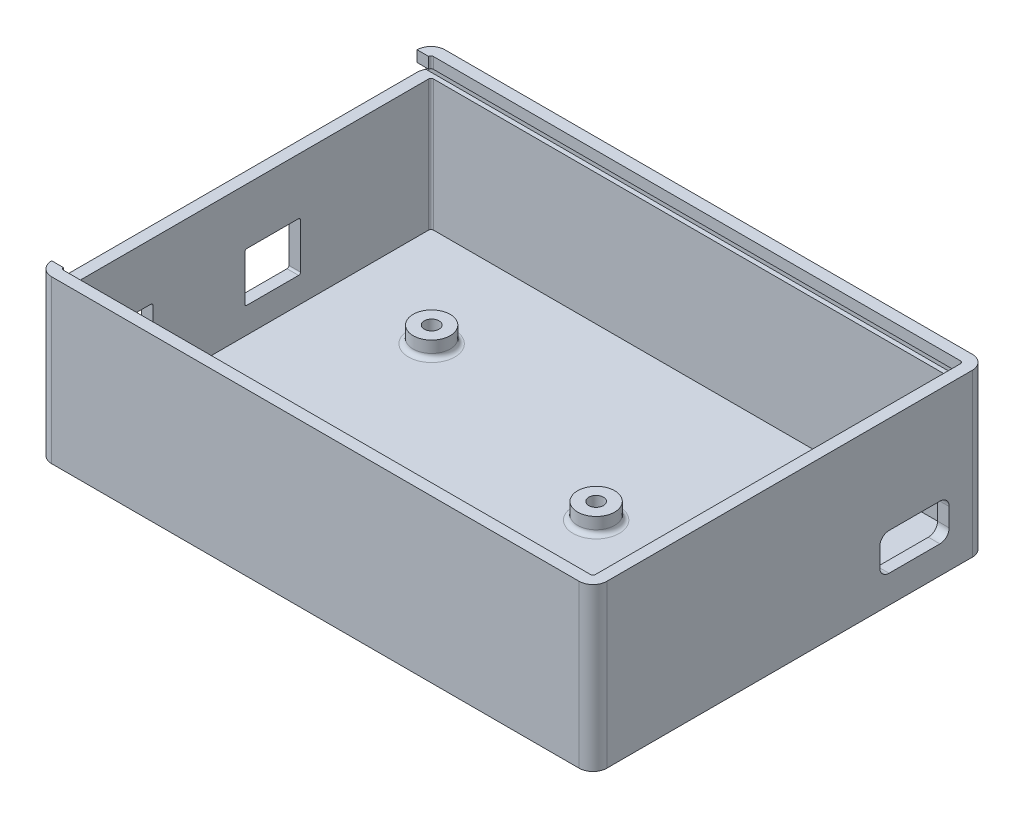
SolidWorks part; units mm, degrees
ref_plane "Front Plane" through (0, 0, 0) normal (0, 0, 1) x (1, 0, 0)
ref_plane "Top Plane" through (0, 0, 0) normal (0, 1, 0) x (1, 0, 0)
ref_plane "Right Plane" through (0, 0, 0) normal (1, 0, 0) x (0, 0, -1)
sketch "Sketch1" plane through (0, 0, 0) normal (0, 1, 0) x (1, 0, 0)
  line L0 (0, 42.5) -> (0, -42.5) construction
  line L1 (60, -42.5) -> (-60, -42.5)
  line L2 (60, -42.5) -> (60, 42.5)
  line L3 (60, 42.5) -> (-60, 42.5)
  line L4 (-60, -42.5) -> (-60, 42.5)
  dimension "D1" = 120
  dimension "D2" = 85
extrude "base extrusion" add sketch "Sketch1" along normal blind 35 contours L4 L3 L2 L1
fillet "external corner fillets" radius 3 4 edges at (-60, 17.5, -42.5) (60, 17.5, -42.5) (60, 17.5, 42.5) (-60, 17.5, 42.5)
shell "enclosure shell" thickness 2.5
sketch "Sketch2" plane through (0, 0, 0) normal (0, -1, 0) x (1, 0, 0)
  line L1 (-50, -21.2) -> (18.6, -21.2) construction
  line L2 (-50, -21.2) -> (-50, 32.5) construction
  line L3 (-50, 32.5) -> (18.6, 32.5) construction
  line L4 (18.6, -21.2) -> (18.6, 32.5) construction
  line L5 (57, 42.5) -> (-57, 42.5) construction
  line L7 (-60, 39.5) -> (-60, -39.5) construction
  line L8 (-35.5925, 29.7194) -> (-38.7675, 29.7194) construction
  line L9 (16.4775, 24.6394) -> (13.3025, 24.6394) construction
  line L10 (16.4775, -3.3006) -> (13.3025, -3.3006) construction
  line L11 (-34.3225, -18.5406) -> (-37.4975, -18.5406) construction
  circle A0 centre (-37.18, 29.7194) radius 1.5875 construction
  circle A1 centre (-37.18, 29.7194) radius 1.5875
  circle A2 centre (14.89, 24.6394) radius 1.5875 construction
  circle A3 centre (14.89, 24.6394) radius 1.5875
  circle A4 centre (14.89, -3.3006) radius 1.5875 construction
  circle A5 centre (14.89, -3.3006) radius 1.5875
  circle A6 centre (-35.91, -18.5406) radius 1.5875 construction
  circle A7 centre (-35.91, -18.5406) radius 1.5875
  circle A8 centre (-37.18, 29.7194) radius 4
  circle A9 centre (14.89, 24.6394) radius 4
  circle A10 centre (14.89, -3.3006) radius 4
  circle A11 centre (-35.91, -18.5406) radius 4
  dimension "D5" = 8
  dimension "D6" = 8
  dimension "D7" = 8
  dimension "D8" = 8
  dimension "D1" = 68.6
  dimension "D2" = 53.7
  dimension "D3" = 10
  dimension "D4" = 10
extrude "arduino mounting holes" add sketch "Sketch2" against normal blind 6
fillet "standoff fillets" radius 1 4 edges at (14.89, 2.5, 20.6394) (14.89, 2.5, -7.3006) (-37.18, 2.5, 25.7194) (-35.91, 2.5, -22.5406)
sketch "Sketch4" plane through (-60, 0, 0) normal (-1, 0, 0) x (0, 0, 1)
  line L0 (20.5844, 18.65) -> (28.5844, 18.65)
  line L1 (29.0844, 18.15) -> (29.0844, 7.65)
  line L2 (29.0844, 7.65) -> (20.0844, 7.65)
  line L3 (20.0844, 7.65) -> (20.0844, 18.15)
  line L4 (-11.3206, 18.7) -> (-0.2006, 18.7)
  line L5 (-0.2006, 18.24) -> (-0.2006, 18.7) construction
  line L6 (-11.7806, 18.24) -> (-11.7806, 8.49)
  line L7 (-0.1506, 8.08) -> (-11.3706, 8.08)
  line L8 (0.2594, 18.24) -> (0.2594, 8.44)
  arc A0 (28.5844, 18.65) -> (29.0844, 18.15) centre (28.5844, 18.15) cw
  arc A1 (20.0844, 18.15) -> (20.5844, 18.65) centre (20.5844, 18.15) cw
  arc A2 (0.2594, 18.24) -> (-0.2006, 18.7) centre (-0.2006, 18.24) ccw construction
  arc A3 (-11.3206, 18.7) -> (-11.7806, 18.24) centre (-11.3206, 18.24) ccw
  arc A4 (-0.2006, 18.7) -> (0.2594, 18.24) centre (-0.2006, 18.24) cw
  arc A5 (-11.7806, 8.49) -> (-11.3706, 8.08) centre (-11.3706, 8.49) ccw
  arc A6 (-0.1506, 8.08) -> (0.2594, 8.44) centre (-0.1506, 8.4935) ccw
extrude "port access hole" cut sketch "Sketch4" against normal blind 6
sketch "Sketch5" plane through (60, 0, 0) normal (1, 0, 0) x (0, 0, -1)
  line L0 (39.5, 0) -> (39.5, 35) construction
  line L1 (34.5, 6) -> (19.5, 6)
  line L2 (34.5, 6) -> (34.5, 14)
  line L3 (34.5, 14) -> (19.5, 14)
  line L4 (19.5, 6) -> (19.5, 14)
  line L5 (-39.5, 0) -> (39.5, 0) construction
  dimension "D1" = 15
  dimension "D2" = 8
  dimension "D3" = 5
  dimension "D4" = 6
extrude "wire access hole" cut sketch "Sketch5" against normal blind 6
fillet "wire access hole fillet" radius 2 4 edges at (58.75, 6, -19.5) (58.75, 6, -34.5) (58.75, 14, -34.5) (58.75, 14, -19.5)
sketch "Sketch6" plane through (0, 2.5, 0) normal (0, 1, 0) x (1, 0, 0)
  line L0 (57, 40) -> (-57, 40) construction
  line L1 (57.5, -39.5) -> (57.5, 39.5) construction
  circle A0 centre (40.7473, 27) radius 2.5
  circle A1 centre (40.7473, 15.7506) radius 2.5
  point P4 (40.7473, 26.9944)
  dimension "D1" = 5
  dimension "D2" = 5
  dimension "D4" = 13
  dimension "D5" = 16.7527
  dimension "D3" = 11.2494
extrude "cable routing posts" add sketch "Sketch6" along normal blind 6
ref_plane "Plane1" through (-60, 0, 0) normal (-1, 0, 0) x (0, 0, 1)
sketch "Sketch10" plane through (-60, 0, 0) normal (-1, 0, 0) x (0, 0, 1)
  line L0 (-42.5, 35) -> (42.5, 35)
  line L1 (42.5, 35) -> (42.5, 0)
  line L2 (42.5, 0) -> (-42.5, 0)
  line L3 (-42.5, 0) -> (-42.5, 35)
  line L4 (-39.5, 35) -> (-39.5, 32.6)
  line L5 (-39.5, 35) -> (-39.5, 0) construction
  line L6 (-39.5, 32.6) -> (-41, 32.6)
  line L7 (-41, 32.6) -> (-41, 30.8)
  line L8 (-41, 30.8) -> (41, 30.8)
  line L9 (39.5, 35) -> (39.5, 32.6)
  line L10 (39.5, 0) -> (39.5, 35) construction
  line L11 (39.5, 32.6) -> (41, 32.6)
  line L12 (41, 32.6) -> (41, 30.8)
  line L13 (-39.5, 35) -> (39.5, 35)
  dimension "D1" = 2.4
  dimension "D2" = 1.5
  dimension "D3" = 2.4
  dimension "D4" = 1.5
  dimension "D5" = 1.8
extrude "lid cut extrude" cut sketch "Sketch10" against normal blind 117.5 contours L6 L7 L8 L12 L11 L9 L13 L4
